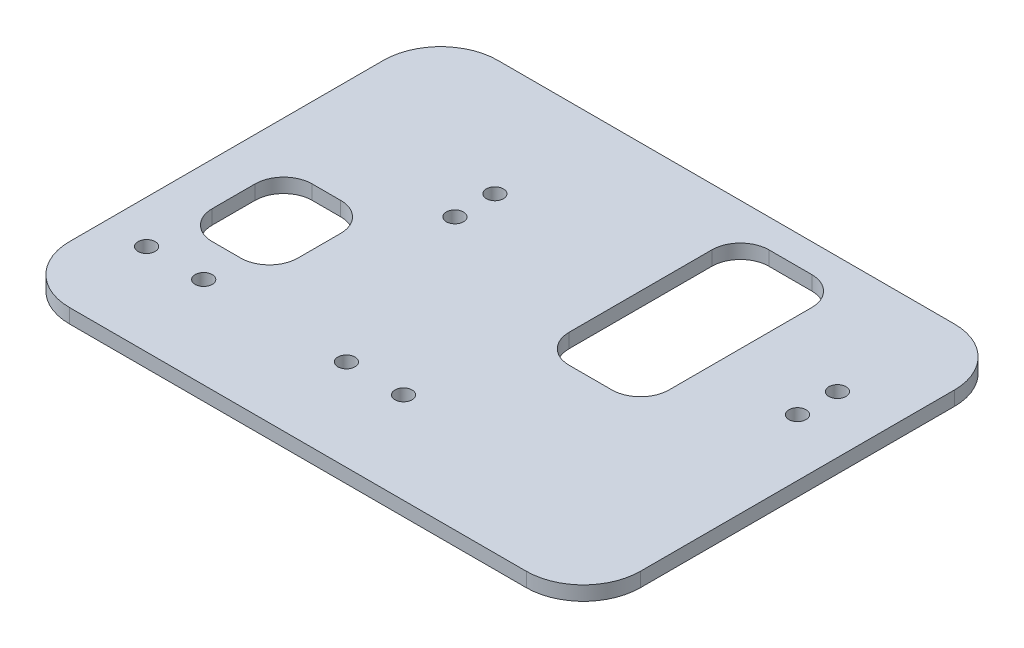
SolidWorks part; units mm, degrees
material "6061-T6 (SS)"
ref_plane "Front Plane" through (0, 0, 0) normal (0, 0, 1) x (1, 0, 0)
ref_plane "Top Plane" through (0, 0, 0) normal (0, 1, 0) x (1, 0, 0)
ref_plane "Right Plane" through (0, 0, 0) normal (1, 0, 0) x (0, 0, -1)
sketch "Sketch1" plane through (0, 0, 0) normal (0, 1, 0) x (1, 0, 0)
  line L1 (-85, 75) -> (115, 75)
  line L2 (-85, 75) -> (-85, -75)
  line L3 (-85, -75) -> (115, -75)
  line L4 (115, 75) -> (115, -75)
  line L5 (-85, 75) -> (115, -75) construction
  line L6 (-85, -75) -> (115, 75) construction
  dimension "D1" = 200
  dimension "D2" = 150
extrude "Boss-Extrude1" add sketch "Sketch1" along normal blind 5 contours L3 L4 L1 L2
sketch "Sketch3" plane through (0, 5, 0) normal (0, 1, 0) x (1, 0, 0)
  line L1 (-85, 75) -> (-85, -75) construction
  line L2 (-85, -75) -> (115, -75) construction
  line L3 (-85, 75) -> (-85, -75) construction
  line L4 (-85, 75) -> (115, 75) construction
  line L5 (40, -5) -> (55, -5)
  line L6 (30, 5) -> (30, 55)
  line L7 (40, 65) -> (55, 65)
  line L8 (65, 5) -> (65, 55)
  line L9 (30, -5) -> (65, 65) construction
  line L10 (30, 65) -> (65, -5) construction
  line L17 (-42.226, 18.71) -> (-40, 15) construction
  line L18 (-60, -30) -> (-50, -30)
  line L19 (-70, -20) -> (-70, -5)
  line L20 (-60, 5) -> (-50, 5)
  line L21 (-40, -20) -> (-40, -5)
  line L22 (-70, -30) -> (-40, 5) construction
  line L23 (115, 75) -> (115, -75) construction
  line L24 (-70, 5) -> (-40, -30) construction
  circle A0 centre (-70, -43) radius 3
  circle A1 centre (-50, -43) radius 3
  circle A2 centre (0, -43) radius 3
  circle A3 centre (20, -43) radius 3
  circle A4 centre (-25, 20) radius 3
  circle A5 centre (-25, 34) radius 3
  circle A6 centre (95, 20) radius 3
  circle A7 centre (95, 34) radius 3
  arc A8 (30, 55) -> (40, 65) centre (40, 55) cw
  arc A9 (55, 65) -> (65, 55) centre (55, 55) cw
  arc A10 (55, -5) -> (65, 5) centre (55, 5) ccw
  arc A11 (40, -5) -> (30, 5) centre (40, 5) cw
  arc A12 (-70, -5) -> (-60, 5) centre (-60, -5) cw
  arc A13 (-50, 5) -> (-40, -5) centre (-50, -5) cw
  arc A14 (-50, -30) -> (-40, -20) centre (-50, -20) ccw
  arc A15 (-60, -30) -> (-70, -20) centre (-60, -20) cw
  point P20 (-73.6316, 9.2516)
  point P33 (47.5, 30)
  point P59 (-55, -12.5)
  dimension "D1" = 32
  dimension "D3" = 6
  dimension "D4" = 6
  dimension "D5" = 6
  dimension "D6" = 6
  dimension "D11" = 6
  dimension "D12" = 6
  dimension "D13" = 6
  dimension "D14" = 6
  dimension "D30" = 10
  dimension "D36" = 10
  dimension "D2" = 15
  dimension "D7" = 20
  dimension "D8" = 20
  dimension "D9" = 50
  dimension "D10" = 14
  dimension "D15" = 120
  dimension "D16" = 60
  dimension "D17" = 41
  dimension "D22" = 35
  dimension "D23" = 30
  dimension "D25" = 15
  dimension "D27" = 35
  dimension "D28" = 10
  dimension "D29" = 50
extrude "Cut-Extrude2" cut sketch "Sketch3" against normal blind 10
fillet "Fillet1" radius 20 4 edges at (115, 2.5, 75) (115, 2.5, -75) (-85, 2.5, -75) (-85, 2.5, 75)
